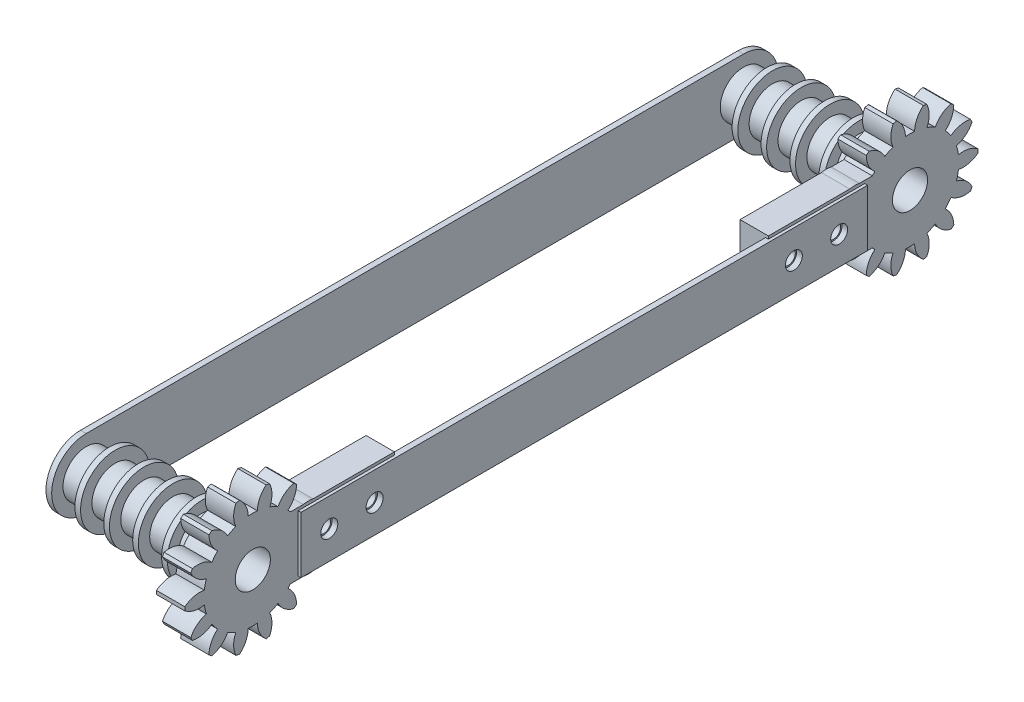
SolidWorks part; units mm, degrees
material "ABS"
ref_plane "Plane1" through (0, 0, 0) normal (0, 0, 1) x (1, 0, 0)
ref_plane "Plane2" through (0, 0, 0) normal (0, 1, 0) x (1, 0, 0)
ref_plane "Plane3" through (0, 0, 0) normal (1, 0, 0) x (0, 0, -1)
other "Configuration Table"
sketch "HoldingSke" plane through (0, 0, 0) normal (0, 1, 0) x (1, 0, 0)
  line L0 (0, 0) -> (0.6469, -0.1613)
  line L1 (-15, 0) -> (100, 0) construction
  line L2 (0, 0) -> (-2.1039, 2.3779)
  line L3 (0, 0) -> (-11.863, 4.5341)
  line L4 (0, 0) -> (8.3795, 2.0892)
  line L5 (0, 0) -> (-46.8476, -17.4728)
  line L6 (0, 0) -> (-4.1448, -2.7965)
  line L7 (-2.1039, 2.3779) -> (8.6586, 51.2059)
  line L8 (-76.2, 54.61) -> (-75.7, 54.61)
  line L9 (-71.009, 38.7566) -> (-53.1078, 45.2721)
  line L10 (-76.2, 71.12) -> (104.1128, 71.12)
  line L11 (0, 0) -> (-5, 0)
  line L12 (-76.2, 101.6) -> (-76.147, 101.6)
  line L13 (24.9733, 27.94) -> (52.9518, 28.4284)
  line L14 (24.9733, 27.94) -> (24.9743, 27.94)
  line L15 (24.9733, 27.94) -> (100.4006, 29.5858)
  line L16 (-63.627, -1.5) -> (-12.827, -1.5)
  circle A0 centre (0, 0) radius 1.5
  circle A1 centre (0, 0) radius 8.624
  circle A2 centre (0, 0) radius 37.5
  circle A3 centre (0, 0) radius 1.5
  dimension "MHD" = 17.248
  dimension "Hub_dia" = 75
  dimension "Bore" = 3
  dimension "MBD" = 3
  dimension "Num_teeth" = 14
  dimension "Pitch" = 0.6667
  dimension "Overall_len" = 50
  dimension "Show_teeth" = 14
  dimension "Thickness" = 5
  dimension "OAL" = 50.0001
  dimension "T_dim" = 0.5
  dimension "Ap" = 20
  dimension "H" = 19.05
  dimension "Pitch_radius" = 180.3128
  dimension "Width" = 5
  dimension "Backlash" = 0.053
  dimension "Addendum_fac" = 1
  dimension "Dedendum_fac" = 1.25
  dimension "Clearance_fac" = 0.25
  dimension "Dedendum_add" = 0.001
  dimension "Module" = 1.5
sketch "BasProSke" plane through (0, 0, 0) normal (0, 1, 0) x (1, 0, 0)
  line L0 (-10, 0) -> (60, 0) construction
  line L1 (0, 0) -> (0, 12)
  line L2 (0, 0) -> (5, 0)
  line L3 (5, 0) -> (5, 12)
  line L4 (5, 12) -> (0, 12)
  dimension "Thickness" = 5
  dimension "Diameter" = 24
revolve "Base-Revolve" add sketch "BasProSke" angle 360 about L0
sketch "TooCutSke" plane through (0, 0, 0) normal (1, 0, 0) x (0, 0, -1)
  line L1 (0, 0) -> (0, 107) construction
  line L2 (0, 0) -> (-1.2683, 10.4231) construction
  line L3 (0, 0) -> (-4.648, 20.3643) construction
  line L4 (-1.2683, 10.4231) -> (-2.324, 10.1822) construction
  arc A0 (0.8048, 8.5864) -> (-0.8048, 8.5864) centre (0, 0) ccw
  arc A1 (2.3844, 11.7866) -> (-2.3844, 11.7866) centre (0, 0) ccw
  circle A2 centre (0, 0) radius 10.5 construction
  circle A3 centre (0, 0) radius 9.8668 construction
  arc A4 (-0.8048, 8.5864) -> (-2.3844, 11.7866) centre (-5.004, 8.5037) ccw
  arc A5 (2.3844, 11.7866) -> (0.8048, 8.5864) centre (5.004, 8.5037) ccw
  dimension "Root_dia" = 17.248
  dimension "Overcut_dia" = 24.0508
  dimension "Pitch_dia" = 21
  dimension "Base_dia" = 19.7335
  dimension "Flank_rad" = 4.2
  dimension "Half_ang" = 12.857
  dimension "Half_CT" = 1.0829
extrude "ToothCut" cut sketch "TooCutSke" along normal through all
fillet "Breaks" [suppressed] radius 0.03
fillet "RootFillets" [suppressed] radius 0.376
pattern_circular "TeethCuts" count 14 every 25.714 about axis through (-10, 0, 0) along (1, 0, 0) of "ToothCut", "RootFillets", "Breaks"
sketch "HubNeaOneSke" plane through (0, 0, 0) normal (-1, 0, 0) x (0, 0, 1)
  circle A0 centre (0, 0) radius 8.624
  dimension "Diameter" = 17.248
extrude "HubNearOne" [suppressed] add sketch "HubNeaOneSke" along normal blind 45.0001
sketch "HubNeaBotSke" plane through (0, 0, 0) normal (-1, 0, 0) x (0, 0, 1)
  circle A0 centre (0, 0) radius 8.624
  dimension "Diameter" = 17.248
extrude "HubNearBoth" [suppressed] add sketch "HubNeaBotSke" along normal blind 22.5
ref_plane "FarPln" through (5, 0, 0) normal (1, 0, 0) x (0, 0, -1)
sketch "HubFarSke" plane through (5, 0, 0) normal (1, 0, 0) x (0, 0, -1)
  circle A0 centre (0, 0) radius 8.624
  dimension "Diameter" = 17.248
extrude "HubFar" [suppressed] add sketch "HubFarSke" along normal blind 22.5
sketch "BorSke" plane through (0, 0, 0) normal (1, 0, 0) x (0, 0, -1)
  circle A0 centre (0, 0) radius 3.1
  dimension "Diameter" = 6.2
extrude "Bore" cut sketch "BorSke" along normal mid plane 100.0001
sketch "KeySke" plane through (0, 0, 0) normal (1, 0, 0) x (0, 0, -1)
  line L0 (-0.6, 0) -> (-0.6, 2)
  line L1 (-0.6, 2) -> (0.6, 2)
  line L2 (0.6, 2) -> (0.6, 0)
  line L3 (0, 0) -> (0, 34) construction
  line L4 (-0.6, 0) -> (0.6, 0)
  dimension "Offset" = 2
  dimension "Width" = 1.2
extrude "Keyway" [suppressed] cut sketch "KeySke" along normal mid plane 100.0001
pattern_circular "Keyway2" [suppressed] count 2 every 90 about axis through (-10, 0, 0) along (1, 0, 0)
sketch "ｽｹｯﾁ2" plane through (5, 0, 0) normal (1, 0, 0) x (0, 0, -1)
  line L0 (5, 5.5) -> (5, -5.5)
  line L1 (5, -5.5) -> (25, -5.5)
  line L2 (25, -5.5) -> (25, 5.5)
  line L3 (25, 5.5) -> (5, 5.5)
  line L4 (0, 0) -> (5, 0) construction
  dimension "D1" = 11
  dimension "D2" = 5
  dimension "D3" = 20
extrude "ﾎﾞｽ - 押し出し1" add sketch "ｽｹｯﾁ2" against normal up to surface (5 mm away) up to face at (0, 0, -3.1)
sketch "ｽｹｯﾁ3" plane through (5, 0, 0) normal (1, 0, 0) x (0, 0, -1)
  line L0 (25, -5.5) -> (25, 5.5) construction
  line L1 (25, -5) -> (8, -5)
  line L2 (25, -5) -> (25, 5)
  line L3 (25, 5) -> (8, 5)
  line L4 (8, -5) -> (8, 5)
  line L5 (8, 0) -> (0, 0) construction
  dimension "D1" = 10
  dimension "D2" = 8
extrude "ｶｯﾄ - 押し出し1" cut sketch "ｽｹｯﾁ3" against normal blind 0.5
sketch "ｽｹｯﾁ5" plane through (0, 0, -8) normal (0, 0, -1) x (-1, 0, 0)
  line L0 (-4.5, 5) -> (-5, 5) construction
  line L1 (-4.5, -5) -> (-14.5, -5)
  line L2 (-4.5, -5) -> (-4.5, 5)
  line L3 (-4.5, 5) -> (-14.5, 5)
  line L4 (-14.5, -5) -> (-14.5, 5)
  line L5 (-5.5, -4) -> (-5.5, 4)
  line L6 (-5.5, 4) -> (-13.5, 4)
  line L7 (-13.5, -4) -> (-13.5, 4)
  line L8 (-5.5, -4) -> (-13.5, -4)
  dimension "D1" = 1
extrude "ﾎﾞｽ - 押し出し2" add sketch "ｽｹｯﾁ5" along normal blind 100 separate body
sketch "ｽｹｯﾁ4" plane through (0, 0, 0) normal (-1, 0, 0) x (0, 0, 1)
  line L0 (0, 0) -> (-25, 0) construction
  line L1 (-25, 5.5) -> (-25, -5.5) construction
  line L2 (-8, 5) -> (-8, -5) construction
  circle A0 centre (-21, 0) radius 1.25
  circle A1 centre (-13, 0) radius 1.25
  dimension "D3" = 2.5
  dimension "D1" = 5
  dimension "D2" = 8
extrude "ｶｯﾄ - 押し出し2" cut sketch "ｽｹｯﾁ4" against normal through all and the other way through all
sketch "ｽｹｯﾁ7" plane through (0, 0, 0) normal (-1, 0, 0) x (0, 0, 1)
  circle A0 centre (0, 0) radius 4.1
  circle A1 centre (0, 0) radius 3.1
  circle A2 centre (0, 0) radius 3.1 construction
  dimension "D2" = 8.2
extrude "ﾎﾞｽ - 押し出し3" add sketch "ｽｹｯﾁ7" along normal blind 4 separate body
sketch "ｽｹｯﾁ9" plane through (-4, 0, 0) normal (-1, 0, 0) x (0, 0, 1)
  circle A0 centre (0, 0) radius 3.1 construction
  circle A1 centre (0, 0) radius 3.1
  circle A2 centre (0, 0) radius 6.1
  circle A3 centre (0, 0) radius 4.1 construction
  dimension "D1" = 2
extrude "ﾎﾞｽ - 押し出し4" add sketch "ｽｹｯﾁ9" along normal blind 1 separate body
ref_plane "平面1" through (0, 0, -58) normal (0, 0, -1) x (-1, 0, 0)
mirror "ﾐﾗｰ2" about plane through (0, 0, -58) normal (0, 0, -1) of bodies 106 111 121
sketch "ｽｹｯﾁ6" plane through (4.5, 0, 0) normal (-1, 0, 0) x (0, 0, 1)
  circle A0 centre (-103, 0) radius 1.5
  circle A1 centre (-95, 0) radius 1.5
  circle A2 centre (-21, 0) radius 1.5
  circle A3 centre (-13, 0) radius 1.5
  dimension "D1" = 3
extrude "ｶｯﾄ - 押し出し3" cut sketch "ｽｹｯﾁ6" against normal through all
pattern_linear "直線ﾊﾟﾀｰﾝ1" count 5 spacing 5.1 along (-1, 0, 0) of bodies 112 111
pattern_linear "直線ﾊﾟﾀｰﾝ2" count 4 spacing 5.1 along (-1, 0, 0) of bodies 121 122
sketch "ｽｹｯﾁ10" plane through (0, 0, -8) normal (0, 0, 1) x (1, 0, 0)
  line L0 (14.5, -5) -> (4.5, -5) construction
  line L1 (5.5, -5) -> (14.5, -5)
  line L2 (5.5, -5) -> (5.5, 5)
  line L3 (5.5, 5) -> (14.5, 5)
  line L4 (14.5, -5) -> (14.5, 5)
  line L6 (5.5, -4) -> (5.5, 4) construction
extrude "ｶｯﾄ - 押し出し4" cut sketch "ｽｹｯﾁ10" against normal up to surface (100 mm away) up to face at (9.5, 0, -108)
sketch "ｽｹｯﾁ12" plane through (-24.4, 0, 0) normal (-1, 0, 0) x (0, 0, 1)
  line L0 (0, 0) -> (-116, 0) construction
  line L1 (0, -6.1) -> (-116, -6.1)
  line L2 (0, 6.1) -> (-116, 6.1)
  arc A0 (0, -6.1) -> (0, 6.1) centre (0, 0) ccw
  arc A1 (-116, 6.1) -> (-116, -6.1) centre (-116, 0) ccw
  circle A2 centre (-116, 0) radius 6.1 construction
  circle A3 centre (0, 0) radius 3.1 construction
  circle A4 centre (-116, 0) radius 3.1 construction
  circle A5 centre (0, 0) radius 3.1
  circle A6 centre (-116, 0) radius 3.1
  point P4 (-58, 0)
extrude "ﾎﾞｽ - 押し出し5" add sketch "ｽｹｯﾁ12" along normal blind 1 separate body
equation "' \"Module@HoldingSke\" = 6.35"
equation "' \"Num_teeth@HoldingSke\" = 12"
equation "' \"Ap@HoldingSke\" =  20"
equation "' \"Ap@HoldingSke\" = 20"
equation "' \"Width@HoldingSke\" = 0.5 * 25.4"
equation "' \"Hub_dia@HoldingSke\"= 1 * 25.4"
equation "' \"Hub_dia@HoldingSke\" = 1 * 25.4"
equation "' \"Overall_len@HoldingSke\" = 1.0 * 25.4"
equation "' \"Bore@HoldingSke\" = 0.75 * 25.4"
equation "' \"T_dim@HoldingSke\" = 0.1 * 25.4"
equation "' \"Width@KeySke\" = 0.25 * 25.4"
equation "' \"Show_teeth@HoldingSke\" = 13"
equation "' \"Backlash@HoldingSke\" = 0.009 * 25.4"
equation "' \"Addendum_fac@HoldingSke\" = 1.0"
equation "' \"Dedendum_fac@HoldingSke\" = 1.25"
equation "' \"Dedendum_add@HoldingSke\" = 0.00005 * 25.4"
equation "' \"Clearance_fac@HoldingSke\" = 0.25"
equation "\"Pitch@HoldingSke\" = 1 / \"Module@HoldingSke\""
equation "\"Overcut_dia@TooCutSke\" = (\"Num_teeth@HoldingSke\" + 2 * \"Addendum_fac@HoldingSke\") / \"Pitch@HoldingSke\" + 0.002 * 25.4"
equation "\"Pitch_dia@TooCutSke\" = \"Num_teeth@HoldingSke\" / \"Pitch@HoldingSke\""
equation "\"Base_dia@TooCutSke\" = \"Num_teeth@HoldingSke\" / \"Pitch@HoldingSke\" * cos((\"Ap@HoldingSke\"  * 3.14159265 / 180))"
equation "\"Root_dia@TooCutSke\" = (\"Num_teeth@HoldingSke\" + 2) / \"Pitch@HoldingSke\" - 2 * (\"Addendum_fac@HoldingSke\" + \"Dedendum_fac@HoldingSke\") / \"Pitch@HoldingSke\" - \"Dedendum_add@HoldingSke\" * 2"
equation "\"Half_ang@TooCutSke\" = 180 / \"Num_teeth@HoldingSke\""
equation "\"Half_CT@TooCutSke\" = \"Num_teeth@HoldingSke\" / \"Pitch@HoldingSke\" * sin((3.14159265 / 2 / \"Num_teeth@HoldingSke\")) / 2 - 7 * \"Backlash@HoldingSke\" / 4"
equation "\"Flank_rad@TooCutSke\" = \"Num_teeth@HoldingSke\" / \"Pitch@HoldingSke\" / 5"
equation "\"Radius@RootFillets\" = \"Clearance_fac@HoldingSke\" / \"Pitch@HoldingSke\" + \"Dedendum_add@HoldingSke\""
equation "\"Break_rad@Breaks\" = 0.02 / \"Pitch@HoldingSke\""
equation "\"Thickness@HoldingSke\" = \"Width@HoldingSke\""
equation "\"OAL@HoldingSke\" = \"Thickness@HoldingSke\""
equation "\"MHD@HoldingSke\" = (\"Num_teeth@HoldingSke\" + 2) / \"Pitch@HoldingSke\" - 2 * (\"Addendum_fac@HoldingSke\" + \"Dedendum_fac@HoldingSke\")  / \"Pitch@HoldingSke\" - \"Dedendum_add@HoldingSke\" * 2"
equation "\"MBD@HoldingSke\" = (\"Num_teeth@HoldingSke\" + 2) / \"Pitch@HoldingSke\" - 2 * (\"Addendum_fac@HoldingSke\" + \"Dedendum_fac@HoldingSke\")  / \"Pitch@HoldingSke\" - \"Dedendum_add@HoldingSke\" * 2 - 0.002 * 25.4"
equation "\"MHD@HoldingSke\" = ((sgn( \"MHD@HoldingSke\" - \"Hub_dia@HoldingSke\" )-1)*( \"MHD@HoldingSke\" - \"Hub_dia@HoldingSke\" ))/-2+ \"Hub_dia@HoldingSke\""
equation "\"MBD@HoldingSke\" = ((sgn( \"MBD@HoldingSke\" - \"Bore@HoldingSke\" )-1)*( \"MBD@HoldingSke\" - \"Bore@HoldingSke\" ))/-2+ \"Bore@HoldingSke\""
equation "\"OAL@HoldingSke\" = ((sgn( \"OAL@HoldingSke\" - \"Overall_len@HoldingSke\" )+1)*( \"OAL@HoldingSke\" - \"Overall_len@HoldingSke\" ))/2 + \"Overall_len@HoldingSke\" + 0.000002 * 25.4"
equation "\"Num_teeth@TeethCuts\" = int( \"Show_teeth@HoldingSke\" ) + 1"
equation "\"Num_teeth@TeethCuts\" = ((sgn( \"Num_teeth@TeethCuts\" - \"Num_teeth@HoldingSke\" )-1)*( \"Num_teeth@TeethCuts\" - \"Num_teeth@HoldingSke\" ))/-2+ \"Num_teeth@HoldingSke\""
equation "\"Num_teeth@TeethCuts\" = ((sgn( \"Num_teeth@TeethCuts\" - 2.0)+1)*( \"Num_teeth@TeethCuts\" - 2.0))/2 +2.0"
equation "\"Angle@TeethCuts\" = 360.0 / \"Num_teeth@HoldingSke\""
equation "\"Diameter@BasProSke\" = (\"Num_teeth@HoldingSke\" + 2 * \"Addendum_fac@HoldingSke\") / \"Pitch@HoldingSke\""
equation "\"Thickness@BasProSke\"  = \"Thickness@HoldingSke\""
equation "' \"Fillet_rad@BasProSke\" =  \"Thickness@HoldingSke\" * 0.05"
equation "' \"Fillet_rad@BasProSke\" = \"Thickness@HoldingSke\" * 0.05"
equation "\"MHD@HoldingSke\" = ((sgn( \"MHD@HoldingSke\" - \"Root_dia@TooCutSke\" )-1)*( \"MHD@HoldingSke\" - \"Root_dia@TooCutSke\" ))/-2+ \"Root_dia@TooCutSke\""
equation "\"Diameter@HubNeaOneSke\" = \"MHD@HoldingSke\""
equation "\"Length@HubNearOne\" = \"OAL@HoldingSke\" - \"Thickness@BasProSke\""
equation "\"Diameter@HubNeaBotSke\" = \"MHD@HoldingSke\""
equation "\"Length@HubNearBoth\" = ( \"OAL@HoldingSke\" - \"Thickness@BasProSke\" ) / 2.0"
equation "\"Thickness@FarPln\" = \"Thickness@BasProSke\""
equation "\"Diameter@HubFarSke\" = \"MHD@HoldingSke\""
equation "\"Length@HubFar\" = ( \"OAL@HoldingSke\" - \"Thickness@BasProSke\" ) / 2.0"
equation "\"D1@Bore\" = \"OAL@HoldingSke\" * 2.0"
equation "\"D1@Keyway\" = \"OAL@HoldingSke\" * 2.0"
equation "\"Offset@KeySke\" = \"T_dim@HoldingSke\" + \"MBD@HoldingSke\" / 2.0"
